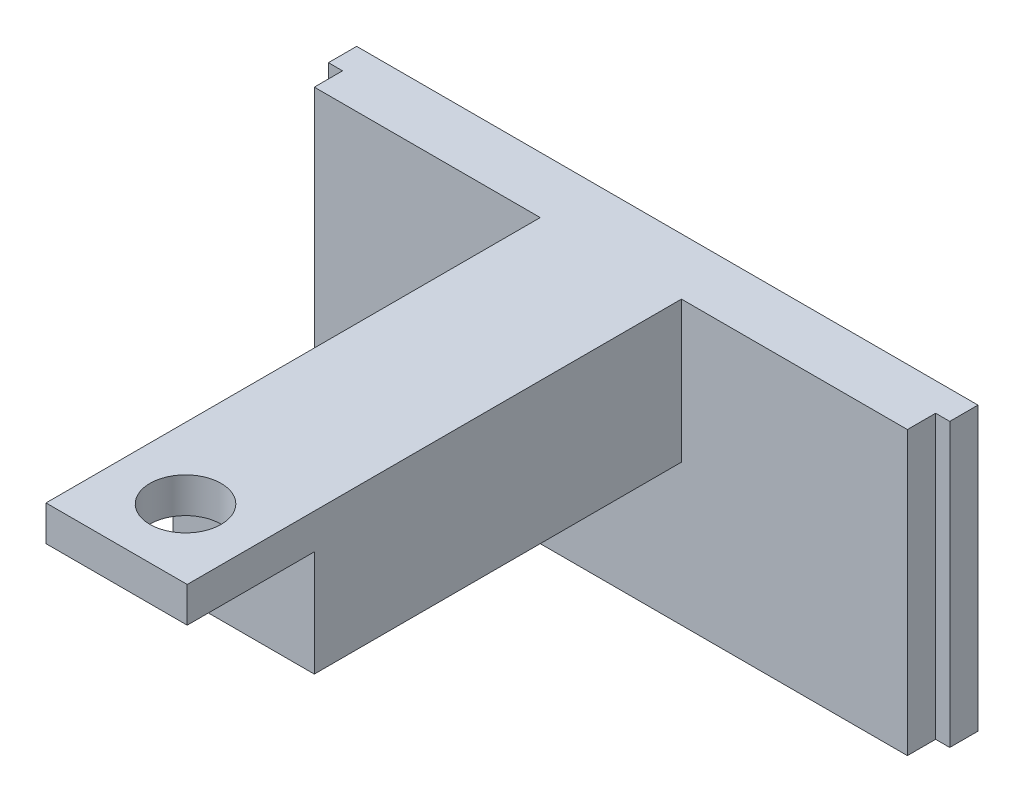
SolidWorks part; units mm, degrees
ref_plane "Ön Düzlem" through (0, 0, 0) normal (0, 0, 1) x (1, 0, 0)
ref_plane "Üst Düzlem" through (0, 0, 0) normal (0, 1, 0) x (1, 0, 0)
ref_plane "Sağ Düzlem" through (0, 0, 0) normal (1, 0, 0) x (0, 0, -1)
sketch "Çizim1" plane through (0, 0, 0) normal (0, 0, 1) x (1, 0, 0)
  line L1 (-22, 10) -> (22, 10)
  line L2 (-22, 10) -> (-22, -10)
  line L3 (-22, -10) -> (22, -10)
  line L4 (22, 10) -> (22, -10)
  line L5 (-22, 10) -> (22, -10) construction
  line L6 (-22, -10) -> (22, 10) construction
  point P0 (0, 0)
  dimension "D1" = 44
  dimension "D2" = 20
extrude "Yükseklik-Ekstrüzyon1" add sketch "Çizim1" along normal blind 2
sketch "Çizim2" plane through (0, 0, 2) normal (0, 0, 1) x (1, 0, 0)
  line L1 (-21, 10) -> (21, 10)
  line L2 (-21, 10) -> (-21, -10)
  line L3 (-21, -10) -> (21, -10)
  line L4 (21, 10) -> (21, -10)
  line L5 (-21, 10) -> (21, -10) construction
  line L6 (-21, -10) -> (21, 10) construction
  point P0 (0, 0)
  dimension "D1" = 42
  dimension "D2" = 20
extrude "Yükseklik-Ekstrüzyon2" add sketch "Çizim2" along normal blind 2
sketch "Çizim3" plane through (0, 0, 4) normal (0, 0, 1) x (1, 0, 0)
  line L0 (21, 10) -> (-21, 10) construction
  line L1 (-5, 10) -> (5, 10)
  line L2 (-5, 10) -> (-5, 0)
  line L3 (-5, 0) -> (5, 0)
  line L4 (5, 10) -> (5, 0)
  line L5 (-5, 10) -> (5, 0) construction
  line L6 (-5, 0) -> (5, 10) construction
  point P0 (0, 5)
  dimension "D1" = 10
  dimension "D2" = 10
  dimension "D3" = 0
  dimension "D4" = 0
extrude "Yükseklik-Ekstrüzyon3" add sketch "Çizim3" along normal blind 35
sketch "Çizim4" plane through (0, 10, 0) normal (0, 1, 0) x (1, 0, 0)
  line L0 (-5, -39) -> (-5, -4) construction
  line L1 (22, 0) -> (-22, 0) construction
  circle A0 centre (0, -34.12) radius 2.52
  dimension "D1" = 5
  dimension "D2" = 34.12
extrude "Kes-Ekstrüzyon1" cut sketch "Çizim4" against normal blind 11
sketch "Çizim5" plane through (0, 0, 39) normal (0, 0, 1) x (1, 0, 0)
  line L0 (-5, 10) -> (-5, 0) construction
  line L1 (-5, 7.5) -> (5, 7.5)
  line L2 (-5, 7.5) -> (-5, 0)
  line L3 (-5, 0) -> (5, 0)
  line L4 (5, 7.5) -> (5, 0)
  line L5 (-5, 7.5) -> (5, 0) construction
  line L6 (-5, 0) -> (5, 7.5) construction
  line L7 (5, 10) -> (-5, 10) construction
  point P0 (0, 3.75)
  dimension "D1" = 10
  dimension "D2" = 7.5
  dimension "D3" = 0
  dimension "D4" = 2.5
extrude "Kes-Ekstrüzyon2" cut sketch "Çizim5" against normal blind 9
